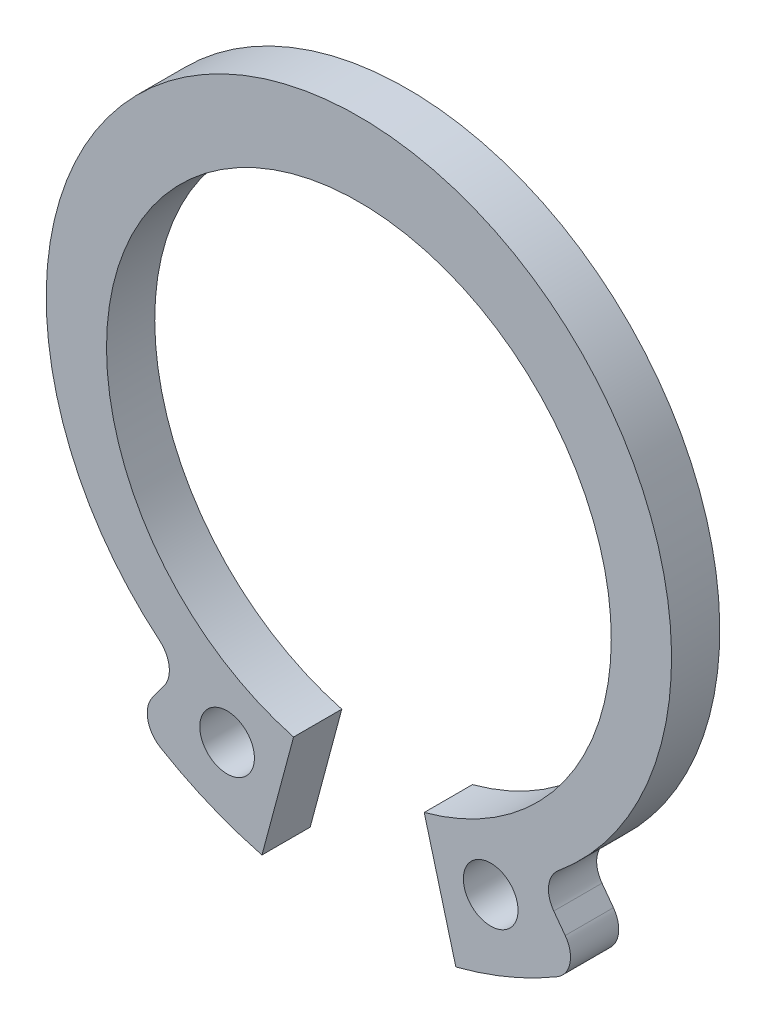
SolidWorks part; units mm, degrees
ref_plane "Plan1" through (0, 0, 0) normal (0, 0, 1) x (1, 0, 0)
ref_plane "Plan2" through (0, 0, 0) normal (0, 1, 0) x (1, 0, 0)
ref_plane "Plan3" through (0, 0, 0) normal (1, 0, 0) x (0, 0, -1)
sketch "Esquisse1" plane through (0, 0, 0) normal (0, 0, 1) x (1, 0, 0)
  line L0 (0, 0) -> (3.0152, -11.253) construction
  line L1 (0, 0) -> (0, -67.082) construction
  line L2 (6.0616, -8.2233) -> (6.4168, -8.7052)
  line L3 (2.0317, -7.5825) -> (3.0152, -11.253)
  line L4 (-2.0317, -7.5825) -> (-3.0152, -11.253)
  line L5 (-6.0616, -8.2233) -> (-6.4168, -8.7052)
  line L6 (2.0317, -7.5825) -> (6.1673, -9.94) construction
  line L7 (0, 0) -> (0, 7.85) construction
  line L8 (0, 7.85) -> (0, 10.15) construction
  arc A0 (2.0317, -7.5825) -> (-2.0317, -7.5825) centre (0, 0) ccw
  arc A1 (3.0152, -11.253) -> (6.1673, -9.94) centre (0, 0.425) ccw
  arc A2 (6.2036, -7.0644) -> (-6.2036, -7.0644) centre (0, 0.425) ccw
  arc A3 (-6.1673, -9.94) -> (-3.0152, -11.253) centre (0, 0.425) ccw
  arc A4 (-6.2036, -7.0644) -> (-6.0616, -8.2233) centre (-6.7459, -7.719) cw
  arc A5 (6.2036, -7.0644) -> (6.0616, -8.2233) centre (6.7459, -7.719) ccw
  circle A6 centre (4.0995, -8.7613) radius 0.85
  circle A7 centre (-4.0995, -8.7613) radius 0.85
  arc A8 (-6.1673, -9.94) -> (-6.4168, -8.7052) centre (-5.7326, -9.2095) cw
  arc A9 (6.1673, -9.94) -> (6.4168, -8.7052) centre (5.7326, -9.2095) ccw
  point P22 (-6.9518, -9.431)
  dimension "D1" = 15.7
  dimension "D2" = 3.8
  dimension "D3" = 2.3
  dimension "D8" = 1.7
  dimension "D4" = 0.425
  dimension "D5" = 4.25
  dimension "a" = 15
extrude "Base-Extrusion" add sketch "Esquisse1" along normal blind 1.5
equation "\"R@Esquisse1\" = \"D8@Esquisse1\"/2"
equation "\"D4@Esquisse1\"=\"R@Esquisse1\"/2"
equation "\"D5@Esquisse1\"=\"D8@Esquisse1\"*2.5"
